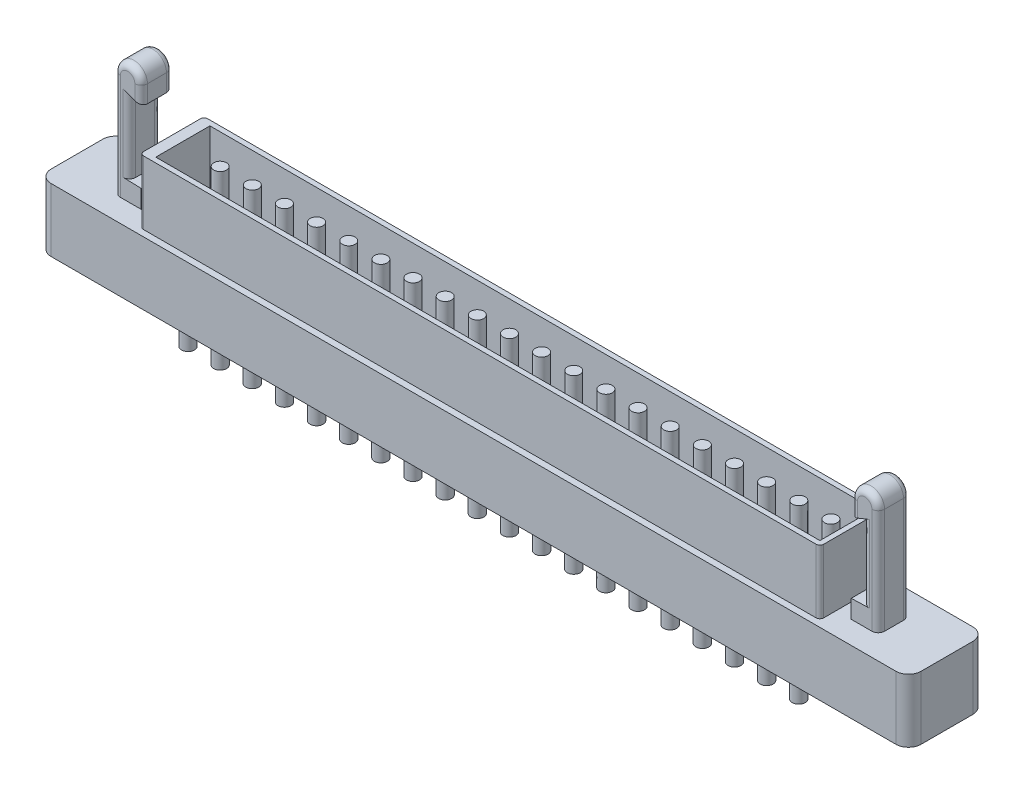
SolidWorks part; units mm, degrees
ref_plane "Спереди" through (0, 0, 0) normal (0, 0, 1) x (1, 0, 0)
ref_plane "Сверху" through (0, 0, 0) normal (0, 1, 0) x (1, 0, 0)
ref_plane "Справа" through (0, 0, 0) normal (1, 0, 0) x (0, 0, -1)
sketch "Эскиз2" plane through (0, 0, 0) normal (0, 0, 1) x (1, 0, 0)
  line L0 (32.05, 7.4474) -> (32.05, -4.0545) construction
  line L1 (0, 0) -> (64.1, 0)
  line L2 (0, 0) -> (0, 2.54)
  line L3 (0, 7.62) -> (64.1, 7.62)
  line L4 (64.1, 0) -> (64.1, 2.54)
  line L5 (19.35, 5) -> (44.75, 5)
  line L6 (19.35, 5) -> (19.35, 6)
  line L7 (19.35, 6) -> (44.75, 6)
  line L8 (44.75, 5) -> (44.75, 6)
  line L9 (64.1, 3.34) -> (64.1, 7.62)
  line L10 (0, 3.34) -> (0.3, 3.34)
  line L12 (0, 2.54) -> (0.3, 2.54)
  line L13 (0.3, 3.34) -> (0.3, 2.54)
  line L14 (64.1, 3.34) -> (63.8, 3.34)
  line L15 (0, 3.34) -> (0, 7.62)
  line L16 (64.1, 2.54) -> (63.8, 2.54)
  line L17 (63.8, 3.34) -> (63.8, 2.54)
  dimension "D1" = 64.1
  dimension "D2" = 7.62
  dimension "D3" = 1
  dimension "D4" = 5
  dimension "D5" = 25.4
  dimension "D6" = 0.3
  dimension "D7" = 0.8
  dimension "D8" = 0.8
  dimension "D9" = 0.3
  dimension "D10" = 2.54
  dimension "D11" = 2.54
extrude "Вытянуть1" add sketch "Эскиз2" along normal blind 5.08
sketch "Эскиз3" plane through (0, 0, 0) normal (0, -1, 0) x (1, 0, 0)
  line L0 (0, 0) -> (64.1, 0) construction
  line L1 (0, 5.08) -> (0, 0) construction
  circle A0 centre (2.54, 3.81) radius 0.5141
  circle A1 centre (2.54, 1.27) radius 0.5024
  dimension "D1" = 2.54
  dimension "D2" = 1.27
  dimension "D3" = 2.54
  dimension "D4" = 2.54
extrude "Вытянуть2" add sketch "Эскиз3" along normal blind 2.5
pattern_linear "Линейный массив1" count 20 spacing 2.54 along (1, 0, 0) of "Вытянуть2"
sketch "Эскиз4" plane through (0, 7.62, 0) normal (0, 1, 0) x (-1, 0, 0)
  line L1 (-71.7953, -1.7915) -> (1.138, -1.7915)
  line L2 (-71.7953, -1.7915) -> (-71.7953, 6.6797)
  line L3 (-71.7953, 6.6797) -> (1.138, 6.6797)
  line L4 (1.138, -1.7915) -> (1.138, 6.6797)
extrude "Вырез-Вытянуть1" cut sketch "Эскиз4" against normal up to surface (5.08 mm away) up to face at (63.95, 2.54, 2.54)
sketch "Эскиз5" plane through (0, 2.54, 0) normal (0, 1, 0) x (-1, 0, 0)
  circle A0 centre (-15.24, 3.81) radius 0.5141 construction
  circle A1 centre (-15.24, 3.81) radius 0.5141
  circle A2 centre (-15.24, 1.27) radius 0.5024 construction
  circle A3 centre (-15.24, 1.27) radius 0.5024
  circle A4 centre (-17.78, 1.27) radius 0.5024 construction
  circle A5 centre (-12.7, 3.81) radius 0.5141 construction
  circle A6 centre (-10.16, 3.81) radius 0.5141 construction
  circle A7 centre (-7.62, 3.81) radius 0.5141 construction
  circle A8 centre (-5.08, 3.81) radius 0.5141 construction
  circle A9 centre (-2.54, 3.81) radius 0.5141 construction
  circle A10 centre (-2.54, 1.27) radius 0.5024 construction
  circle A11 centre (-5.08, 1.27) radius 0.5024 construction
  circle A12 centre (-7.62, 1.27) radius 0.5024 construction
  circle A13 centre (-10.16, 1.27) radius 0.5024 construction
  circle A14 centre (-12.7, 1.27) radius 0.5024 construction
  circle A15 centre (-17.78, 1.27) radius 0.5024
  circle A16 centre (-17.78, 3.81) radius 0.5141 construction
  circle A17 centre (-17.78, 3.81) radius 0.5141
  circle A18 centre (-20.32, 3.81) radius 0.5141 construction
  circle A19 centre (-20.32, 3.81) radius 0.5141
  circle A20 centre (-20.32, 1.27) radius 0.5024 construction
  circle A21 centre (-20.32, 1.27) radius 0.5024
  circle A22 centre (-22.86, 1.27) radius 0.5024 construction
  circle A23 centre (-22.86, 1.27) radius 0.5024
  circle A24 centre (-40.64, 1.27) radius 0.5024 construction
  circle A25 centre (-12.7, 3.81) radius 0.5141
  circle A26 centre (-10.16, 3.81) radius 0.5141
  circle A27 centre (-7.62, 3.81) radius 0.5141
  circle A28 centre (-5.08, 3.81) radius 0.5141
  circle A29 centre (-2.54, 3.81) radius 0.5141
  circle A30 centre (-2.54, 1.27) radius 0.5024
  circle A31 centre (-5.08, 1.27) radius 0.5024
  circle A32 centre (-7.62, 1.27) radius 0.5024
  circle A33 centre (-10.16, 1.27) radius 0.5024
  circle A34 centre (-12.7, 1.27) radius 0.5024
  circle A35 centre (-22.86, 3.81) radius 0.5141
  circle A36 centre (-22.86, 3.81) radius 0.5141
  circle A37 centre (-25.4, 3.81) radius 0.5141
  circle A38 centre (-25.4, 3.81) radius 0.5141
  circle A39 centre (-27.94, 1.27) radius 0.5024
  circle A40 centre (-27.94, 1.27) radius 0.5024
  circle A41 centre (-25.4, 1.27) radius 0.5024
  circle A42 centre (-25.4, 1.27) radius 0.5024
  circle A43 centre (-30.48, 1.27) radius 0.5024
  circle A44 centre (-30.48, 1.27) radius 0.5024
  circle A45 centre (-30.48, 3.81) radius 0.5141
  circle A46 centre (-30.48, 3.81) radius 0.5141
  circle A47 centre (-27.94, 3.81) radius 0.5141
  circle A48 centre (-27.94, 3.81) radius 0.5141
  circle A49 centre (-33.02, 3.81) radius 0.5141
  circle A50 centre (-33.02, 3.81) radius 0.5141
  circle A51 centre (-33.02, 1.27) radius 0.5024
  circle A52 centre (-33.02, 1.27) radius 0.5024
  circle A53 centre (-35.56, 3.81) radius 0.5141
  circle A54 centre (-35.56, 3.81) radius 0.5141
  circle A55 centre (-35.56, 1.27) radius 0.5024
  circle A56 centre (-35.56, 1.27) radius 0.5024
  circle A57 centre (-38.1, 3.81) radius 0.5141
  circle A58 centre (-38.1, 3.81) radius 0.5141
  circle A59 centre (-38.1, 1.27) radius 0.5024
  circle A60 centre (-38.1, 1.27) radius 0.5024
  circle A62 centre (-50.8, 3.81) radius 0.5141
  circle A63 centre (-40.64, 1.27) radius 0.5024
  circle A64 centre (-50.8, 3.81) radius 0.5141
  circle A65 centre (-43.18, 1.27) radius 0.5024
  circle A66 centre (-43.18, 1.27) radius 0.5024
  circle A67 centre (-43.18, 3.81) radius 0.5141
  circle A68 centre (-43.18, 3.81) radius 0.5141
  circle A69 centre (-40.64, 3.81) radius 0.5141
  circle A70 centre (-40.64, 3.81) radius 0.5141
  circle A71 centre (-45.72, 3.81) radius 0.5141
  circle A72 centre (-45.72, 3.81) radius 0.5141
  circle A73 centre (-45.72, 1.27) radius 0.5024
  circle A74 centre (-45.72, 1.27) radius 0.5024
  circle A75 centre (-48.26, 1.27) radius 0.5024
  circle A76 centre (-48.26, 1.27) radius 0.5024
  circle A77 centre (-48.26, 3.81) radius 0.5141
  circle A78 centre (-48.26, 3.81) radius 0.5141
  circle A79 centre (-50.8, 1.27) radius 0.5024
  circle A80 centre (-50.8, 1.27) radius 0.5024
  dimension "D1" = 0
  dimension "D2" = 0
  dimension "D3" = 0
  dimension "D4" = 0
  dimension "D5" = 0
  dimension "D6" = 0
  dimension "D7" = 0
  dimension "D8" = 0
  dimension "D9" = 0
  dimension "D10" = 0
  dimension "D11" = 0
  dimension "D12" = 0
  dimension "D13" = 0
  dimension "D14" = 0
  dimension "D15" = 0
  dimension "D16" = 0
  dimension "D17" = 0
  dimension "D18" = 0
  dimension "D19" = 0
  dimension "D20" = 0
  dimension "D21" = 0
  dimension "D22" = 0
extrude "Вытянуть3" add sketch "Эскиз5" along normal blind 6
sketch "Эскиз6" plane through (0, 0, 0) normal (0, -1, 0) x (1, 0, 0)
  line L0 (0, 5.08) -> (64.1, 5.08) construction
  line L1 (-5, 5.58) -> (69.1, 5.58)
  line L2 (-5, 5.58) -> (-5, -0.5)
  line L3 (-5, -0.5) -> (69.1, -0.5)
  line L4 (69.1, 5.58) -> (69.1, -0.5)
  line L5 (0, 0) -> (64.1, 0) construction
  line L6 (64.1, 5.08) -> (64.1, 0) construction
  line L7 (0, 5.08) -> (0, 0) construction
  dimension "D1" = 0.5
  dimension "D2" = 0.5
  dimension "D3" = 5
  dimension "D4" = 5
extrude "Вытянуть4" add sketch "Эскиз6" against normal blind 2.4
sketch "Эскиз7" plane through (0, 2.54, 0) normal (0, 1, 0) x (-1, 0, 0)
  line L0 (-53.34, 4.68) -> (-53.34, 0.4)
  line L1 (-0.8606, 4.68) -> (-53.34, 4.68)
  line L2 (-0.8606, 4.68) -> (-0.8606, 0.4)
  line L3 (-0.8606, 0.4) -> (-53.34, 0.4)
  line L4 (-64.1, 0) -> (0, 0)
  line L5 (-53.74, 0) -> (0, 0)
  line L6 (0, 0) -> (0, 5.08)
  line L7 (0, 0) -> (0, 5.08)
  line L8 (0, 5.08) -> (-64.1, 5.08)
  line L9 (0, 5.08) -> (-53.74, 5.08)
  line L10 (-64.1, 5.08) -> (-64.1, 0)
  line L13 (-53.74, 5.08) -> (-53.74, 0)
  circle A0 centre (-50.8, 1.27) radius 0.5024 construction
  dimension "D2" = 2.54
  dimension "D3" = 0.4
  dimension "D1" = 0
extrude "Вытянуть6" add sketch "Эскиз7" along normal blind 7.5
sketch "Эскиз8" plane through (0, 2.4, 0) normal (0, 1, 0) x (-1, 0, 0)
  line L4 (5, -0.5) -> (5, 5.58)
  line L5 (5, 5.58) -> (-69.1, 5.58)
  line L6 (-69.1, 5.58) -> (-69.1, -0.5)
  line L7 (-69.1, -0.5) -> (5, -0.5)
  line L8 (5, -0.5) -> (5, 5.58)
  line L9 (5, 5.58) -> (-69.1, 5.58)
  line L10 (-69.1, 5.58) -> (-69.1, -0.5)
  line L11 (-69.1, -0.5) -> (5, -0.5)
  dimension "D1" = 0
extrude "Вытянуть7" add sketch "Эскиз8" along normal blind 2.6
ref_plane "Плоскость1" through (0, 0, 2.54) normal (0, 0, 1) x (1, 0, 0)
sketch "Эскиз9" plane through (0, 0, 2.54) normal (0, 0, 1) x (1, 0, 0)
  line L0 (26.87, 15.9279) -> (26.87, 2.2251) construction
  line L1 (-3.3209, 2.2251) -> (-1.1831, 2.2251)
  line L2 (-3.3209, 2.2251) -> (-3.3209, 13.3476)
  line L3 (0, 10.04) -> (0, 5) construction
  line L4 (-1.1831, 2.2251) -> (-1.1831, 6.4366)
  line L5 (53.74, 10.04) -> (53.74, 5) construction
  line L6 (54.9231, 11.9785) -> (54.9231, 13.3476)
  line L7 (55.8526, 6.4647) -> (54.9231, 6.4366)
  line L8 (55.8526, 12.3474) -> (55.8526, 6.4647)
  line L11 (-1.1831, 11.9785) -> (-2.1126, 12.3474)
  line L12 (-2.1126, 12.3474) -> (-2.1126, 6.4647)
  line L13 (-2.1126, 6.4647) -> (-1.1831, 6.4366)
  line L14 (54.9231, 11.9785) -> (55.8526, 12.3474)
  line L15 (54.9231, 2.2251) -> (54.9231, 6.4366)
  line L16 (57.0609, 2.2251) -> (57.0609, 13.3476)
  line L17 (57.0609, 2.2251) -> (54.9231, 2.2251)
  line L18 (-1.1831, 11.9785) -> (-1.1831, 13.3476)
  arc A0 (-3.3209, 13.3476) -> (-1.1831, 13.3476) centre (-2.252, 13.3476) cw
  arc A1 (57.0609, 13.3476) -> (54.9231, 13.3476) centre (55.992, 13.3476) ccw
extrude "Вытянуть8" add sketch "Эскиз9" along normal blind 1.25 and the other way blind 1.25
fillet "Скругление1" radius 0.3 4 edges at (0, 7.52, 5.08) (0, 7.52, 0) (53.74, 7.52, 0) (53.74, 7.52, 5.08)
fillet "Скругление2" radius 0.5 16 edges at (-1.1831, 12.6631, 1.29) (-2.252, 14.4165, 1.29) (-1.1831, 12.6631, 3.79) (-2.252, 14.4165, 3.79) (-2.1126, 9.4061, 3.79) (-2.1126, 9.4061, 1.29) (-3.3209, 9.1738, 1.29) (-3.3209, 9.1738, 3.79) (54.9231, 12.6631, 1.29) (55.992, 14.4165, 1.29) (54.9231, 12.6631, 3.79) (55.992, 14.4165, 3.79) (55.8526, 9.4061, 1.29) (55.8526, 9.4061, 3.79) (57.0609, 9.1738, 1.29) (57.0609, 9.1738, 3.79)
sketch "Эскиз10" plane through (69.1, 0, 0) normal (1, 0, 0) x (0, 0, -1)
  line L4 (-5.58, 0) -> (0.5, 0)
  line L5 (0.5, 0) -> (0.5, 5)
  line L6 (0.5, 5) -> (-5.58, 5)
  line L7 (-5.58, 5) -> (-5.58, 0)
  line L8 (-5.58, 0) -> (0.5, 0)
  line L9 (0.5, 0) -> (0.5, 5)
  line L10 (0.5, 5) -> (-5.58, 5)
  line L11 (-5.58, 5) -> (-5.58, 0)
  dimension "D1" = 0
extrude "Вырез-Вытянуть2" cut sketch "Эскиз10" against normal offset from surface (10.36 mm away) 5 up to face at (53.74, 7.52, 2.54)
sketch "Эскиз11" plane through (58.74, 0, 0) normal (1, 0, 0) x (0, 0, -1)
  line L4 (-5.58, 5) -> (-5.58, 0)
  line L5 (-5.58, 0) -> (0.5, 0)
  line L6 (0.5, 0) -> (0.5, 5)
  line L7 (0.5, 5) -> (-5.58, 5)
  line L8 (-5.58, 5) -> (-5.58, 0)
  line L9 (-5.58, 0) -> (0.5, 0)
  line L10 (0.5, 0) -> (0.5, 5)
  line L11 (0.5, 5) -> (-5.58, 5)
  dimension "D1" = 0
extrude "Вытянуть9" add sketch "Эскиз11" along normal blind 2.5
sketch "Эскиз12" plane through (-5, 0, 0) normal (-1, 0, 0) x (0, 0, 1)
  line L4 (-0.5, 0) -> (5.58, 0)
  line L5 (5.58, 0) -> (5.58, 5)
  line L6 (5.58, 5) -> (-0.5, 5)
  line L7 (-0.5, 5) -> (-0.5, 0)
  line L8 (-0.5, 0) -> (5.58, 0)
  line L9 (5.58, 0) -> (5.58, 5)
  line L10 (5.58, 5) -> (-0.5, 5)
  line L11 (-0.5, 5) -> (-0.5, 0)
  dimension "D1" = 0
extrude "Вытянуть10" add sketch "Эскиз12" along normal blind 2.5
fillet "Скругление3" radius 1 4 edges at (61.24, 2.5, 5.58) (61.24, 2.5, -0.5) (-7.5, 2.5, -0.5) (-7.5, 2.5, 5.58)
